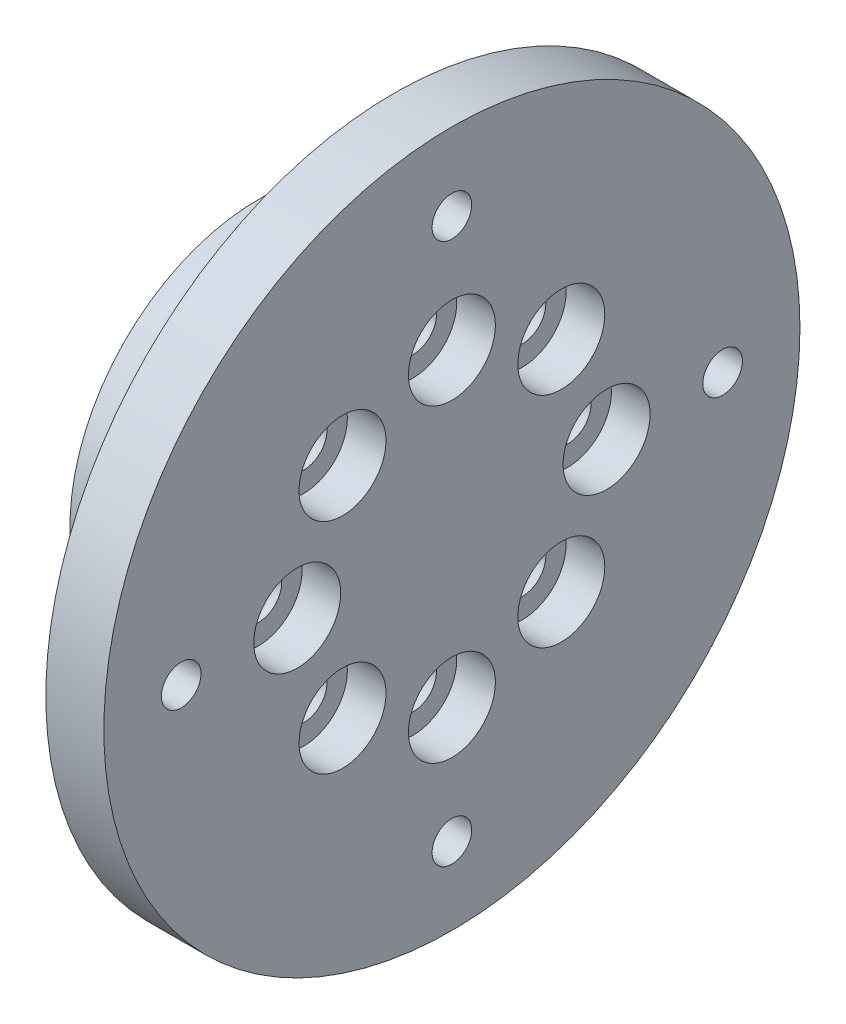
SolidWorks part; units mm, degrees
ref_plane "정면" through (0, 0, 0) normal (0, 0, 1) x (1, 0, 0)
ref_plane "윗면" through (0, 0, 0) normal (0, 1, 0) x (1, 0, 0)
ref_plane "우측면" through (0, 0, 0) normal (1, 0, 0) x (0, 0, -1)
sketch "Sketch1" plane through (0, 0, 0) normal (1, 0, 0) x (0, 0, -1)
  line L0 (0, 0) -> (0, 92.3469) construction
  circle A0 centre (0, 0) radius 9.75
  dimension "D1" = 19.5
extrude "Boss-Extrude1" add sketch "Sketch1" along normal blind 10 contours A0
sketch "Sketch2" plane through (10, 0, 0) normal (1, 0, 0) x (0, 0, -1)
  circle A0 centre (0, 0) radius 8 construction
  circle A1 centre (0, 0) radius 9.75
  point P3 (0, 8)
  point P5 (0, 0)
  point P6 (5.6569, 5.6569)
  point P7 (8, 0)
  point P8 (5.6569, -5.6569)
  point P9 (0, -8)
  point P10 (-5.6569, -5.6569)
  point P11 (-8, 0)
  point P12 (-5.6569, 5.6569)
  point P13 (0, 0)
  point P15 (0, 0)
  dimension "D1" = 16
  dimension "D3" = 19.5
  dimension "D2" = 8
ref_plane "Plane2" through (7, 0, 0) normal (1, 0, 0) x (0, 0, -1)
sketch "Sketch6" plane through (7, 0, 0) normal (1, 0, 0) x (0, 0, -1)
  circle A0 centre (0, 0) radius 18
  dimension "D1" = 36
extrude "Boss-Extrude2" add sketch "Sketch6" along normal blind 3 contours A0
hole_wizard "CBORE for M2 Socket Head Cap Screw5" positions "3DSketch8" profile "Sketch12" counterbore size "M2" standard "KS" end condition through all
sketch3d "3DSketch8"
  point P0 (10, 8, 0)
  point P4 (10, 5.6569, -5.6569)
  point P7 (10, 0, -8)
  point P10 (10, -5.6569, -5.6569)
  point P13 (10, -8, 0)
  point P16 (10, -5.6569, 5.6569)
  point P19 (10, 0, 8)
  point P22 (10, 5.6569, 5.6569)
sketch "Sketch12" plane through (10, 8, 0) normal (0, 1, 0) x (0, 0, -1)
  line L0 (0, 0) -> (0, 10)
  line L1 (0, 10) -> (1.2, 10)
  line L3 (1.2, 10) -> (1.2, 2)
  line L4 (1.2, 2) -> (2.25, 2)
  line L5 (2.25, 2) -> (2.25, 0)
  line L7 (2.25, 0) -> (0, 0)
  line L11 (0, -6.35) -> (0, 107.95) construction
  dimension "Thru Hole Dia." = 2.4
  dimension "Thru Hole Depth" = 10
  dimension "C'Bore Dia." = 4.5
  dimension "C'Bore Depth" = 2
sketch "Sketch14" plane through (0, 0, 0) normal (-1, 0, 0) x (0, 0, 1)
  circle A0 centre (0, 0) radius 4
  dimension "D1" = 8
extrude "Cut-Extrude1" cut sketch "Sketch14" against normal blind 2.2
sketch "Sketch16" plane through (2.2, 0, 0) normal (1, 0, 0) x (0, 0, -1)
  circle A0 centre (0, 0) radius 2.5
  dimension "D1" = 5
sketch "Sketch19" plane through (10, 0, 0) normal (1, 0, 0) x (0, 0, -1)
  circle A0 centre (0, 0) radius 14 construction
  point P3 (0, 14)
  point P4 (0, -14)
  point P5 (-14, 0)
  point P6 (14, 0)
  dimension "D1" = 28
hole_wizard "M2.5 Tapped Hole1" positions "3DSketch13" profile "Sketch21" tap size "M2.5" standard "KS" end condition through all
sketch3d "3DSketch13"
  point P0 (10, 14, 0)
  point P3 (10, 0, -14)
  point P6 (10, -14, 0)
  point P9 (10, 0, 14)
sketch "Sketch21" plane through (10, 14, 0) normal (0, 1, 0) x (0, 0, -1)
  line L0 (0, 0) -> (0, 10)
  line L1 (0, 10) -> (1.025, 10)
  line L2 (1.025, 10) -> (1.025, 0)
  line L5 (1.025, 0) -> (0, 0)
  line L11 (0, -6.35) -> (0, 107.95) construction
  dimension "Thru Tap Drill Dia." = 2.05
  dimension "Thru Tap Drill Depth" = 10
cosmetic thread "Hole Thread1" parameters "D2"=2.5
cosmetic thread "Hole Thread2" parameters "D2"=2.5
cosmetic thread "Hole Thread3" parameters "D2"=2.5
cosmetic thread "Hole Thread4" parameters "D2"=2.5
extrude "Cut-Extrude2" cut sketch "Sketch16" along normal blind 3
